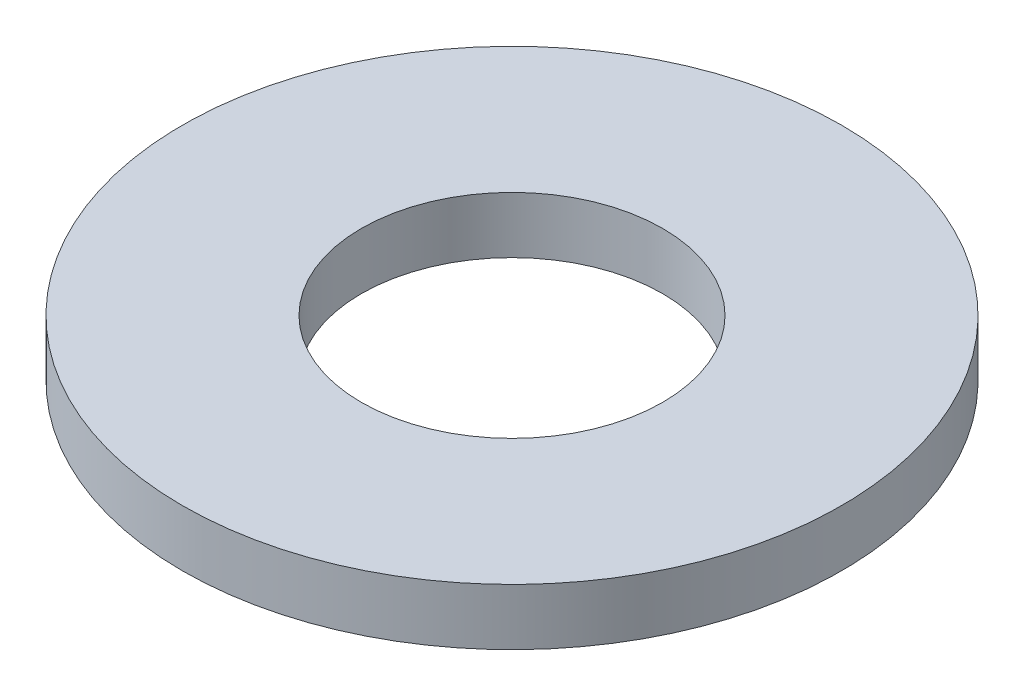
SolidWorks part; units mm, degrees
ref_plane "Front Plane" through (0, 0, 0) normal (0, 0, 1) x (1, 0, 0)
ref_plane "Top Plane" through (0, 0, 0) normal (0, 1, 0) x (1, 0, 0)
ref_plane "Right Plane" through (0, 0, 0) normal (1, 0, 0) x (0, 0, -1)
sketch "Sketch1" plane through (0, 0, 0) normal (0, 1, 0) x (1, 0, 0)
  circle A0 centre (0, 0) radius 7
extrude "Boss-Extrude1" add sketch "Sketch1" along normal blind 1.2
sketch "Sketch2" plane through (0, 1.2, 0) normal (0, 1, 0) x (1, 0, 0)
  circle A0 centre (0, 0) radius 3.2
extrude "Cut-Extrude1" cut sketch "Sketch2" against normal through all
